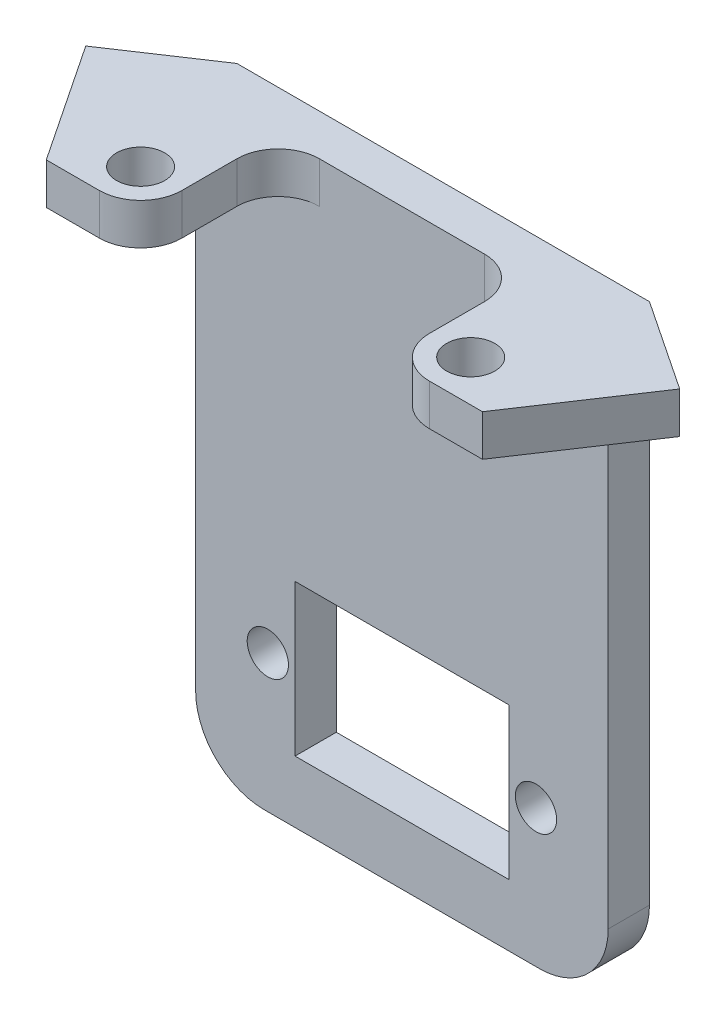
SolidWorks part; units mm, degrees
ref_plane "Front Plane" through (0, 0, 0) normal (0, 0, 1) x (1, 0, 0)
ref_plane "Top Plane" through (0, 0, 0) normal (0, 1, 0) x (1, 0, 0)
ref_plane "Right Plane" through (0, 0, 0) normal (1, 0, 0) x (0, 0, -1)
sketch "Sketch1" plane through (0, 0, 0) normal (0, 0, 1) x (1, 0, 0)
  line L1 (-12.5, -10) -> (12.5, -10)
  line L2 (-12.5, -10) -> (-12.5, 10)
  line L3 (-12.5, 10) -> (12.5, 10)
  line L4 (12.5, -10) -> (12.5, 10)
  line L5 (-12.5, -10) -> (12.5, 10) construction
  line L6 (-12.5, 10) -> (12.5, -10) construction
  circle A0 centre (-9.75, 0) radius 1.5
  circle A1 centre (9.75, 0) radius 1.5
  point P0 (0, 0)
  dimension "D3" = 19.5
  dimension "D4" = 9.75
  dimension "D5" = 3
  dimension "D6" = 3
  dimension "D7" = 10
  dimension "D8" = 10
  dimension "D1" = 20
  dimension "D2" = 25
extrude "Boss-Extrude1" add sketch "Sketch1" along normal blind 3
sketch "Sketch2" plane through (0, 0, 3) normal (0, 0, 1) x (1, 0, 0)
  line L0 (8, 5.5) -> (-8, 5.5) construction
  line L1 (-7.77, 5.5) -> (7.77, 5.5)
  line L2 (-7.77, 5.5) -> (-7.77, -5.5)
  line L3 (-7.77, -5.5) -> (7.77, -5.5)
  line L4 (7.77, 5.5) -> (7.77, -5.5)
  line L5 (8, -5.5) -> (-8, -5.5) construction
  line L6 (-8, 5.5) -> (-8, 2.75) construction
  line L7 (8, 5.5) -> (8, 2.75) construction
  dimension "D1" = 0.23
  dimension "D2" = 0.23
extrude "Cut-Extrude1" cut sketch "Sketch2" against normal through all
sketch "Sketch4" plane through (0, 10, 0) normal (0, 1, 0) x (1, 0, 0)
  line L4 (12.5, 0) -> (-12.5, 0)
  line L5 (-12.5, 0) -> (-12.5, -3)
  line L6 (-12.5, -3) -> (12.5, -3)
  line L7 (12.5, -3) -> (12.5, 0)
  line L8 (12.5, 0) -> (-12.5, 0)
  line L9 (-12.5, 0) -> (-12.5, -3)
  line L10 (-12.5, -3) -> (12.5, -3)
  line L11 (12.5, -3) -> (12.5, 0)
  dimension "D1" = 0
extrude "Boss-Extrude2" add sketch "Sketch4" along normal blind 3
sketch "Sketch5" plane through (0, 0, 3) normal (0, 0, 1) x (1, 0, 0)
  line L0 (12.5, -10) -> (12.5, 13) construction
  line L1 (-12.5, 13) -> (12.5, 13)
  line L2 (-12.5, 13) -> (-12.5, 10)
  line L3 (-12.5, 10) -> (12.5, 10)
  line L4 (12.5, 13) -> (12.5, 10)
  dimension "D1" = 3
extrude "Boss-Extrude3" add sketch "Sketch5" along normal blind 10
sketch "Sketch11" plane through (0, 13, 0) normal (0, 1, 0) x (1, 0, 0)
  line L4 (12.5, -13) -> (12.5, 0)
  line L5 (12.5, 0) -> (-12.5, 0)
  line L6 (-12.5, 0) -> (-12.5, -13)
  line L7 (-12.5, -13) -> (12.5, -13)
  line L8 (12.5, -13) -> (12.5, 0)
  line L9 (12.5, 0) -> (-12.5, 0)
  line L10 (-12.5, 0) -> (-12.5, -13)
  line L11 (-12.5, -13) -> (12.5, -13)
  dimension "D1" = 0
extrude "Boss-Extrude5" add sketch "Sketch11" along normal blind 20
sketch "Sketch12" plane through (0, 10, 0) normal (0, -1, 0) x (1, 0, 0)
  line L4 (-12.5, 3) -> (12.5, 3)
  line L5 (12.5, 3) -> (12.5, 13)
  line L6 (12.5, 13) -> (-12.5, 13)
  line L7 (-12.5, 13) -> (-12.5, 3)
  line L8 (-12.5, 3) -> (12.5, 3)
  line L9 (12.5, 3) -> (12.5, 13)
  line L10 (12.5, 13) -> (-12.5, 13)
  line L11 (-12.5, 13) -> (-12.5, 3)
  dimension "D1" = 0
extrude "Cut-Extrude4" cut sketch "Sketch12" against normal blind 20
sketch "Sketch13" plane through (-12.5, 0, 0) normal (-1, 0, 0) x (0, 0, 1)
  line L6 (3, -10) -> (3, 30)
  line L7 (3, 30) -> (13, 30)
  line L8 (13, 30) -> (13, 33)
  line L9 (13, 33) -> (0, 33)
  line L10 (0, 33) -> (0, -10)
  line L11 (0, -10) -> (3, -10)
  line L12 (3, -10) -> (3, 30)
  line L13 (3, 30) -> (13, 30)
  line L14 (13, 30) -> (13, 33)
  line L15 (13, 33) -> (0, 33)
  line L16 (0, 33) -> (0, -10)
  line L17 (0, -10) -> (3, -10)
  dimension "D1" = 0
extrude "Boss-Extrude6" add sketch "Sketch13" along normal blind 2.5
sketch "Sketch14" plane through (12.5, 0, 0) normal (1, 0, 0) x (0, 0, -1)
  line L6 (-13, 30) -> (-3, 30)
  line L7 (-3, 30) -> (-3, -10)
  line L8 (-3, -10) -> (0, -10)
  line L9 (0, -10) -> (0, 33)
  line L10 (0, 33) -> (-13, 33)
  line L11 (-13, 33) -> (-13, 30)
  line L12 (-13, 30) -> (-3, 30)
  line L13 (-3, 30) -> (-3, -10)
  line L14 (-3, -10) -> (0, -10)
  line L15 (0, -10) -> (0, 33)
  line L16 (0, 33) -> (-13, 33)
  line L17 (-13, 33) -> (-13, 30)
  dimension "D1" = 0
extrude "Boss-Extrude7" add sketch "Sketch14" along normal blind 2.5
sketch "Sketch16" plane through (0, 30, 0) normal (0, -1, 0) x (1, 0, 0)
  line L0 (15, 13) -> (-15, 13) construction
  line L1 (-15, 3) -> (-15, 13) construction
  line L2 (15, 13) -> (15, 3) construction
  circle A0 centre (-12, 10) radius 1.75
  circle A1 centre (12, 10) radius 1.75
  dimension "D1" = 3
  dimension "D2" = 3
  dimension "D3" = 3.5
  dimension "D4" = 3
  dimension "D5" = 3
  dimension "D6" = 3.5
extrude "Cut-Extrude5" cut sketch "Sketch16" against normal through all
fillet "Fillet6" radius 3 1 edges at (-15, 31.5, 13)
fillet "Fillet7" radius 3 1 edges at (15, 31.5, 13)
sketch "Sketch17" plane through (0, 30, 0) normal (0, -1, 0) x (1, 0, 0)
  line L0 (-9, 10) -> (-9, 6)
  line L1 (-15, 3) -> (15, 3) construction
  line L2 (-6, 3) -> (6, 3)
  line L3 (0, 0) -> (0, -3.2471) construction
  line L4 (-15, 0) -> (15, 0) construction
  line L5 (9, 10) -> (9, 6)
  line L6 (12, 13) -> (-12, 13) construction
  line L7 (12, 13) -> (-12, 13)
  arc A0 (-9, 10) -> (-12, 13) centre (-12, 10) ccw
  arc A1 (-9, 6) -> (-6, 3) centre (-6, 6) ccw
  arc A2 (9, 10) -> (12, 13) centre (12, 10) cw
  arc A3 (9, 6) -> (6, 3) centre (6, 6) cw
  dimension "D1" = 6
  dimension "D2" = 3
extrude "Cut-Extrude6" cut sketch "Sketch17" against normal through all
fillet "Fillet8" radius 5 2 edges at (-15, -10, 1.5) (15, -10, 1.5)
sketch "Sketch18" plane through (0, 30, 0) normal (0, -1, 0) x (1, 0, 0)
  line L0 (-12, 13) -> (-15.8575, 13)
  line L1 (-15.8575, 13) -> (-21.5936, 4.3958)
  line L2 (-53.7386, 25.8257) -> (-15, 0) construction
  line L3 (-21.5936, 4.3958) -> (-15, 0)
  line L4 (-15, 0) -> (-15, 10)
  line L5 (-21.5936, 8.0013) -> (-23.2577, 5.5052) construction
  line L6 (0, 0) -> (0, -1.6414) construction
  line L7 (12, 13) -> (15.8575, 13)
  line L8 (15.8575, 13) -> (21.5936, 4.3958)
  line L9 (21.5936, 4.3958) -> (15, 0)
  line L10 (15, 0) -> (15, 10)
  arc A0 (-9, 10) -> (-15, 10) centre (-12, 10) ccw construction
  arc A1 (-12, 13) -> (-15, 10) centre (-12, 10) ccw
  arc A2 (12, 13) -> (15, 10) centre (12, 10) cw
  dimension "D1" = 2
extrude "Boss-Extrude8" add sketch "Sketch18" against normal blind 3
